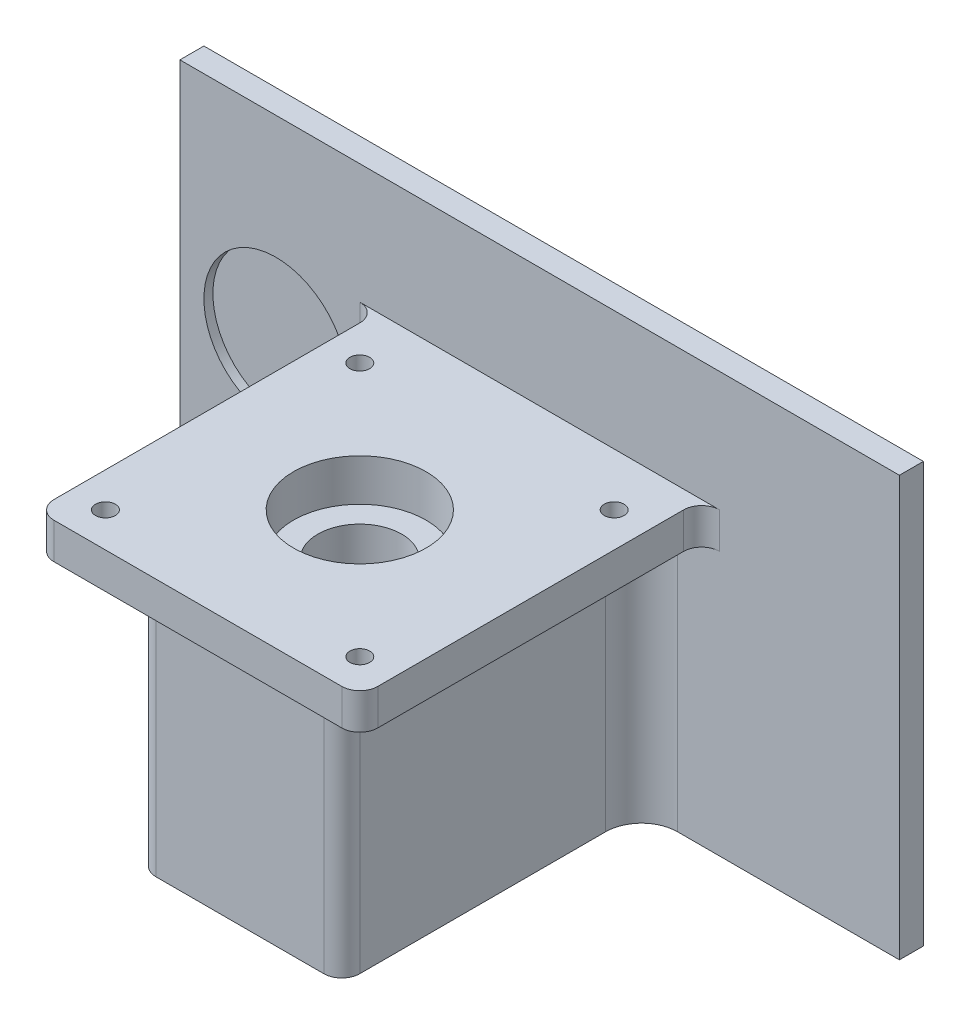
SolidWorks part; units mm, degrees
ref_plane "Front Plane" through (0, 0, 0) normal (1, 0, 0) x (0, 1, 0)
ref_plane "Top Plane" through (0, 0, 0) normal (0, 0, 1) x (0, 1, 0)
ref_plane "Right Plane" through (0, 0, 0) normal (0, 1, 0) x (-1, 0, 0)
sketch "Sketch1" plane through (0, 0, 0) normal (0, 0, 1) x (0, 1, 0)
  line L1 (-35, 60) -> (35, 60)
  line L2 (-35, 60) -> (-35, -60)
  line L3 (-35, -60) -> (35, -60)
  line L4 (35, 60) -> (35, -60)
  line L5 (-35, 60) -> (35, -60) construction
  line L6 (-35, -60) -> (35, 60) construction
  point P0 (0, 0)
  dimension "D1" = 70
  dimension "D2" = 120
extrude "Boss-Extrude1" add sketch "Sketch1" along normal blind 4
sketch "Sketch2" plane through (0, 0, 4) normal (0, 0, 1) x (1, 0, 0)
  line L0 (-60, -35) -> (60, -35) construction
  line L1 (-17, 15) -> (17, 15)
  line L2 (-17, 15) -> (-17, -35)
  line L3 (-17, -35) -> (17, -35)
  line L4 (17, 15) -> (17, -35)
  line L5 (-17, 15) -> (17, -35) construction
  line L6 (-17, -35) -> (17, 15) construction
  point P0 (0, -10)
  dimension "D1" = 34
  dimension "D2" = 50
extrude "Boss-Extrude2" add sketch "Sketch2" along normal blind 50
sketch "Sketch3" plane through (0, -35, 0) normal (0, -1, 0) x (1, 0, 0)
  line L0 (-17, 54) -> (17, 54) construction
  circle A0 centre (0, 34) radius 11.1
  dimension "D1" = 22.2
  dimension "D2" = 20
extrude "Cut-Extrude1" cut sketch "Sketch3" against normal blind 7
sketch "Sketch5" plane through (0, -28, 0) normal (0, -1, 0) x (1, 0, 0)
  circle A0 centre (0, 34) radius 7
  dimension "D1" = 14
extrude "Cut-Extrude3" cut sketch "Sketch5" against normal through all
sketch "Sketch6" plane through (0, 15, 0) normal (0, 1, 0) x (-1, 0, 0)
  circle A0 centre (0, 34) radius 11.05
  dimension "D1" = 22.1
extrude "Cut-Extrude4" cut sketch "Sketch6" against normal blind 7
sketch "Sketch7" plane through (0, 0, 4) normal (0, 0, 1) x (1, 0, 0)
  line L0 (17, -35) -> (60, -35) construction
  line L2 (-60, 35) -> (-60, -35) construction
  circle A0 centre (-44, 2.5) radius 12
  dimension "D1" = 24
  dimension "D3" = 16
  dimension "D2" = 37.5
extrude "Cut-Extrude5" cut sketch "Sketch7" against normal blind 1.5
sketch "Sketch8" plane through (0, 15, 0) normal (0, 1, 0) x (-1, 0, 0)
  line L5 (-17, 4) -> (-27, 4)
  line L6 (-60, 4) -> (60, 4) construction
  line L11 (-21.2132, 12.7868) -> (21.2132, 55.2132) construction
  line L12 (-21.2132, 55.2132) -> (21.2132, 12.7868) construction
  line L13 (-21.2132, 55.2132) -> (-21.2132, 12.7868) construction
  line L14 (-21.2132, 12.7868) -> (21.2132, 12.7868) construction
  line L16 (-27, 4) -> (-27, 61)
  line L17 (-27, 61) -> (27, 61)
  line L18 (27, 61) -> (27, 4)
  line L19 (27, 4) -> (17, 4)
  line L20 (17, 4) -> (17, 54)
  line L21 (17, 54) -> (-17, 54)
  line L22 (-17, 54) -> (-17, 4)
  circle A0 centre (-21.2132, 55.2132) radius 1.65
  circle A1 centre (21.2132, 55.2132) radius 1.65
  circle A2 centre (-21.2132, 12.7868) radius 1.65
  circle A3 centre (21.2132, 12.7868) radius 1.65
  point P0 (0, 34)
  point P6 (0, 61)
  point P21 (0, 34)
  dimension "D3" = 3.3
  dimension "D1" = 54
  dimension "D2" = 27
  dimension "D4" = 60
extrude "Boss-Extrude3" add sketch "Sketch8" against normal blind 6
fillet "Fillet1" radius 3 6 edges at (-27, 12, 4) (27, 12, 4) (27, 12, 61) (-27, 12, 61) (-17, -13, 54) (17, -13, 54)
fillet "Fillet2" radius 6 2 edges at (17, -13, 4) (-17, -13, 4)
